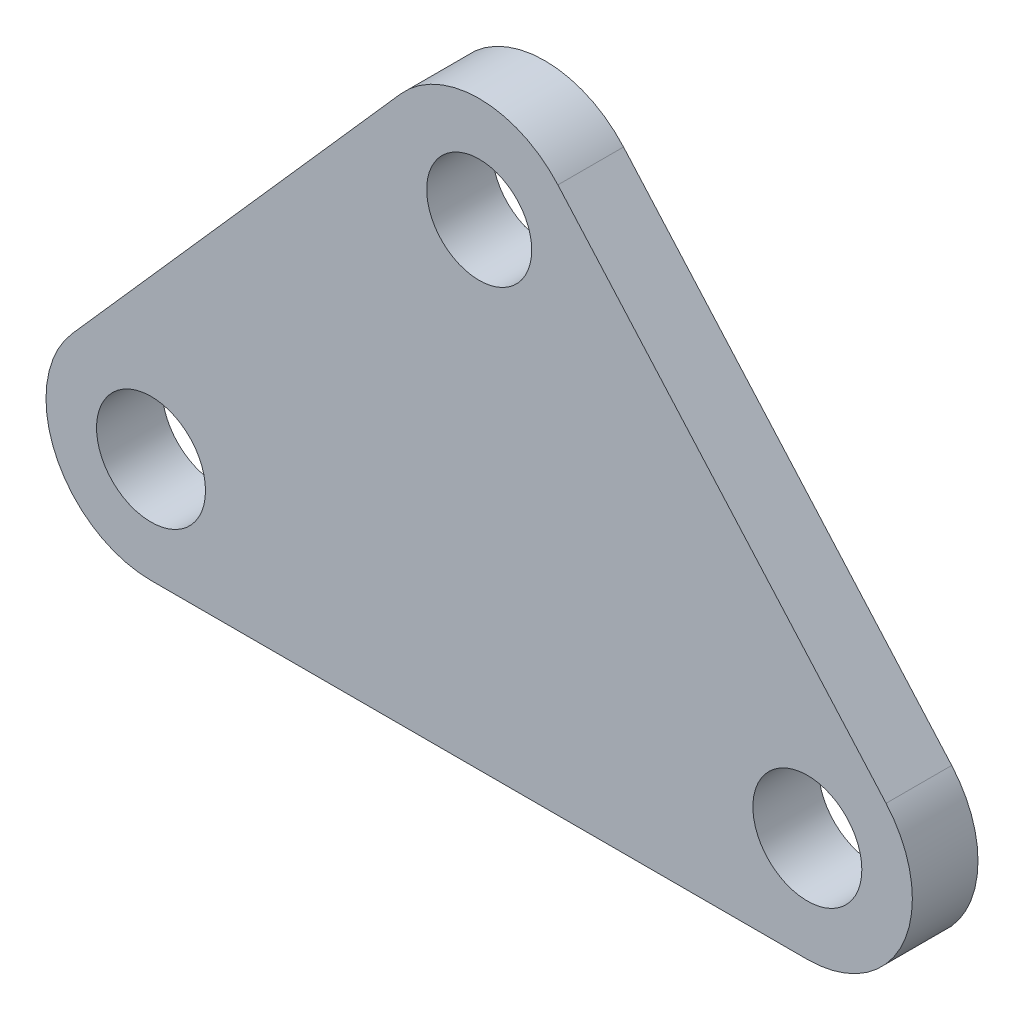
SolidWorks part; units mm, degrees
material "ABS"
ref_plane "Front Plane" through (0, 0, 0) normal (0, 0, 1) x (1, 0, 0)
ref_plane "Top Plane" through (0, 0, 0) normal (0, 1, 0) x (1, 0, 0)
ref_plane "Right Plane" through (0, 0, 0) normal (1, 0, 0) x (0, 0, -1)
sketch "Sketch1" plane through (0, 0, 0) normal (0, 0, 1) x (1, 0, 0)
  line L0 (0, 27.2364) -> (0, -32.7408) construction
  line L1 (25, -36.3) -> (-25, -36.3)
  line L2 (-30.9956, -23.0035) -> (-5.9956, 5.2965)
  line L3 (30.9956, -23.0035) -> (5.9956, 5.2965)
  line L4 (-25, -20.3) -> (25, -20.3)
  circle A0 centre (0, 0) radius 4
  circle A1 centre (0, 0) radius 11 construction
  circle A2 centre (-25, -28.3) radius 4.15
  arc A3 (-25, -36.3) -> (-30.9956, -23.0035) centre (-25, -28.3) cw
  arc A4 (-5.9956, 5.2965) -> (5.9956, 5.2965) centre (0, 0) cw
  arc A5 (25, -36.3) -> (30.9956, -23.0035) centre (25, -28.3) ccw
  circle A6 centre (25, -28.3) radius 4.15
  arc A7 (-25, -20.3) -> (-30.9956, -23.0035) centre (-25, -28.3) ccw
  arc A8 (25, -20.3) -> (30.9956, -23.0035) centre (25, -28.3) cw
  point P8 (0, 11)
  point P15 (0, -36.3)
  point P21 (0, -20.3)
  dimension "D1" = 8
  dimension "D2" = 22
  dimension "D3" = 8.3
  dimension "D6" = 8
  dimension "D7" = 8
  dimension "D4" = 25
  dimension "D5" = 39.3
extrude "Boss-Extrude2" add sketch "Sketch1" against normal blind 5 contours L4 A8 L3 A4 L2 A7 A0 | A8 L4 A7 A3 L1 A5 A2 A6
equation "\"rod_diameter\"= 8"
equation "\"rod_hole_thickness\"= 4"
equation "\"rod_radius\"= \"rod_diameter\" / 2"
equation "\"platter_diameter\"= 320"
equation "\"platter_radius\"= \"platter_diameter\" / 2"
equation "\"extruder_mount_hole_spacing\"= 75"
equation "\"arm_rod_spacing\"= 40"
equation "\"motor_level_rod_spacing\"= 15"
equation "\"linear_bearing_diameter\"= 15"
equation "\"z_rod_spacing\"= 75"
equation "\"platter_rod_spacing\"= 50"
equation "\"rod_nut_thickness\"= 6.5"
equation "\"rod_nut_inscribed_diameter\"= 13"
equation "\"z_height\"= 400"
equation "\"D1@Sketch1\"=\"rod_diameter\""
equation "\"D3@Sketch1\"=\"rod_diameter\"+\"printed_hole_tolerance\""
equation "\"D4@Sketch1\"=\"platter_rod_spacing\"/2"
equation "\"D6@Sketch1\"=\"rod_radius\"+\"rod_hole_thickness\""
equation "\"D7@Sketch1\"=\"rod_radius\"+\"rod_hole_thickness\""
equation "\"top_frame_spacing\"= 100"
equation "\"z_drive_rod_offset\"= 12"
equation "\"gear_pitch\"=2"
equation "\"r_gear_teeth\"= 450"
equation "\"theta_gear_teeth\"= 385"
equation "\"sheet_thickness\"=5.333"
equation "\"sheet_tab_hole_thickness\"= \"sheet_thickness\""
equation "\"sheet_tab_width\"= \"sheet_thickness\"*2"
equation "\"sheet_double_tab_width\"= 35"
equation "\"sheet_bolt_diameter\"= 3"
equation "\"sheet_bolt_length\"= 16"
equation "\"sheet_nut_diameter\"= 5.5"
equation "\"sheet_nut_thickness\"= 2.5"
equation "\"sheet_nut_depth\"= 10"
equation "\"bearing_outside_diameter\"= 22"
equation "\"bearing_thickness\"= 7"
equation "\"corner_part_thickness\"= \"sheet_thickness\" + \"bearing_thickness\""
equation "\"setscrew_nut_diameter\"= 6"
equation "\"setscrew_nut_thickness\"= 3"
equation "\"setscrew_bolt_diameter\"= 3"
equation "\"motor_shaft_diameter\"= 5.7"
equation "\"printed_hole_tolerance\"= 0.3"
